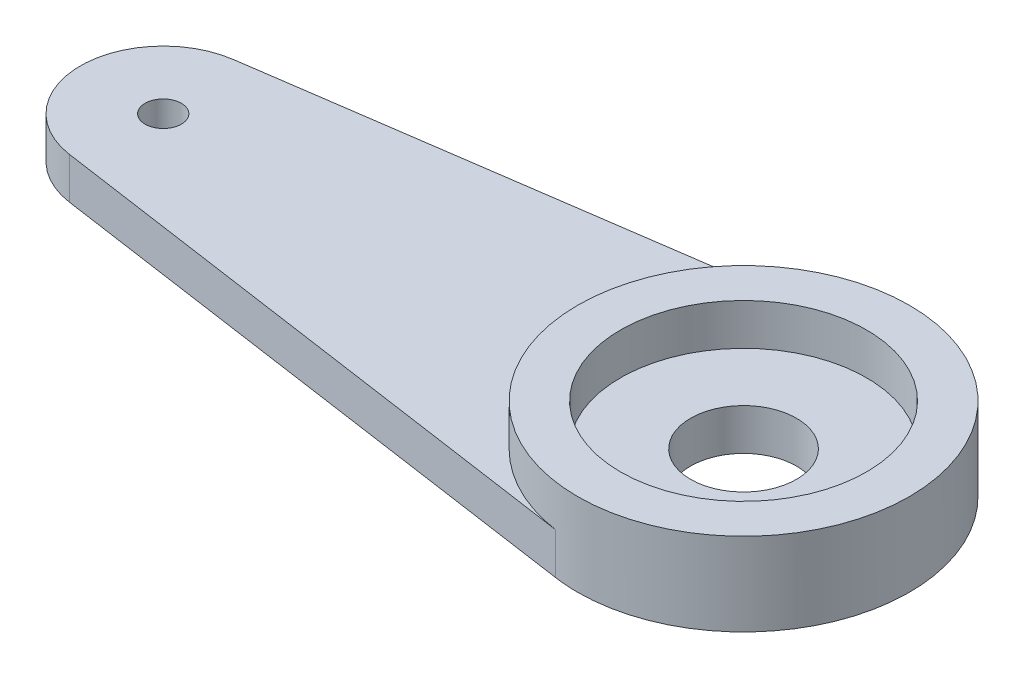
SolidWorks part; units mm, degrees
ref_plane "Front Plane" through (0, 0, 0) normal (0, 0, 1) x (1, 0, 0)
ref_plane "Top Plane" through (0, 0, 0) normal (0, 1, 0) x (1, 0, 0)
ref_plane "Right Plane" through (0, 0, 0) normal (1, 0, 0) x (0, 0, -1)
sketch "Sketch1" plane through (0, 0, 0) normal (0, 1, 0) x (1, 0, 0)
  line L0 (0, 0) -> (88.9, 0) construction
  line L1 (-1.8143, 12.5697) -> (85.2714, 25.1395)
  line L2 (-1.8143, -12.5697) -> (85.2714, -25.1395)
  arc A0 (-1.8143, 12.5697) -> (-1.8143, -12.5697) centre (0, 0) ccw
  arc A1 (85.2714, -25.1395) -> (85.2714, 25.1395) centre (88.9, 0) ccw
  dimension "D2" = 25.4
  dimension "D3" = 50.8
  dimension "length" = 88.9
extrude "Extrude1" add sketch "Sketch1" against normal blind 6.35
sketch "Sketch2" plane through (0, 0, 0) normal (0, 1, 0) x (1, 0, 0)
  circle A0 centre (88.9, 0) radius 25.4
extrude "Extrude2" add sketch "Sketch2" along normal blind 6.35
hole_wizard "7/32 (0.21875) Diameter Hole1" positions "3DSketch2" profile "Sketch4" hole size "7/32" standard "Ansi Inch"
sketch3d "3DSketch2"
  line L2 (-12.7, 0, 0) -> (0, 0, 0)
  line L4 (-12.7, 0, 0) -> (0, 0, 0)
  line L5 (0, -6.35, 0) -> (0, 0, 0) construction
  arc A1 (-1.8143, 0, -12.5697) -> (-1.8143, 0, 12.5697) centre (0, 0, 0) ccw construction
  point P0 (0, 0, 0)
  point P7 (0, 0, 0)
  point P25 (0, 12.7, 0)
  dimension "D1" = 12.7
sketch "Sketch4" plane through (0, 0, 0) normal (1, 0, 0) x (0, 0, 1)
  line L0 (0, 0) -> (0, 27.0693)
  line L1 (0, 27.0693) -> (2.7781, 25.4)
  line L2 (2.7781, 25.4) -> (2.7781, 0)
  line L5 (2.7781, 0) -> (0, 0)
  line L10 (0, 27.0693) -> (-2.7781, 25.4) construction
  line L11 (0, -6.35) -> (0, 107.95) construction
  dimension "Hole Dia." = 5.5562
  dimension "Hole Depth" = 25.4
  dimension "Drill Angle" = 118
ref_plane "Plane1" through (0, 6.35, 0) normal (0, 1, 0) x (-1, 0, 0)
sketch "Sketch5" plane through (0, 6.35, 0) normal (0, 1, 0) x (-1, 0, 0)
  arc A0 (-85.2714, -25.1395) -> (-85.2714, 25.1395) centre (-88.9, 0) ccw construction
  circle A4 centre (-88.9, 0) radius 18.8487
extrude "Extrude3" cut sketch "Sketch5" against normal blind 6.35
ref_plane "Plane2" through (0, 0, 0) normal (0, 1, 0) x (-1, 0, 0)
sketch "Sketch6" plane through (0, 0, 0) normal (0, 1, 0) x (-1, 0, 0)
  circle A0 centre (-88.9, 0) radius 18.8487 construction
  circle A2 centre (-88.9, 0) radius 8.1135
extrude "Extrude5" cut sketch "Sketch6" against normal through all
